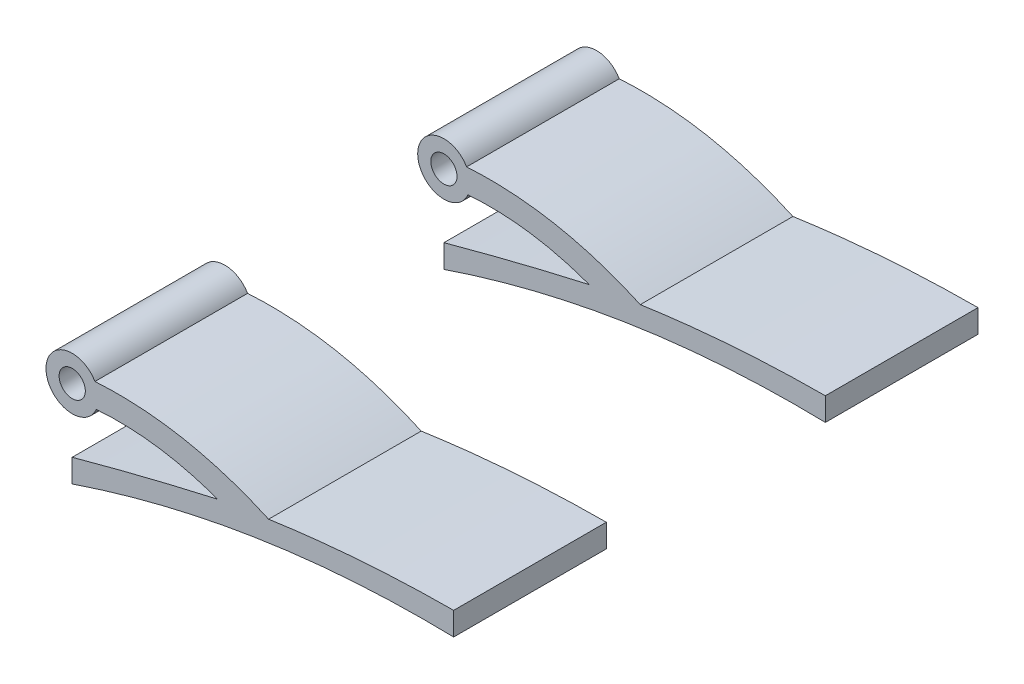
SolidWorks part; units mm, degrees
ref_plane "Front Plane" through (0, 0, 0) normal (0, 0, 1) x (1, 0, 0)
ref_plane "Top Plane" through (0, 0, 0) normal (0, 1, 0) x (1, 0, 0)
ref_plane "Right Plane" through (0, 0, 0) normal (1, 0, 0) x (0, 0, -1)
sketch "Sketch1" plane through (0, 0, 0) normal (0, 0, 1) x (1, 0, 0)
  circle A0 centre (0, 0) radius 25.4
  circle A1 centre (0, 0) radius 12.7
  dimension "D1" = 25.4
  dimension "D2" = 50.8
extrude "Boss-Extrude1" add sketch "Sketch1" along normal mid plane 508
sketch "Sketch3" plane through (0, 0, 0) normal (0, 0, 1) x (1, 0, 0)
  line L2 (0, -61.8729) -> (0, -84.2795)
  line L3 (369.5689, -5.5169) -> (369.5689, -27.9235)
  circle A0 centre (0, 0) radius 25.4 construction
  arc A2 (23.3186, -10.07) -> (21.997, 12.7) centre (0, 0) ccw
  spline S0 degree 2 poles (21.997, 12.7) (108.7753, 18.1925) (190.252, -18.7129) knots 0 0 0 1 1 1
  spline S1 degree 2 poles (23.3186, -10.07) (83.505, -5.4823) (140.7493, -26.6579) knots 0 0 0 1 1 1
  spline S2 degree 2 poles (190.252, -18.7129) (278.7121, -5.8166) (369.5689, -5.5169) knots 0.521873 0.521873 0.521873 1 1 1
  spline S3 degree 2 poles (0, -84.2795) (179.1543, -23.5221) (369.5689, -27.9235) knots 0 0 0 1 1 1
  spline S4 degree 2 poles (0, -61.8729) (69.9758, -42.6269) (140.7493, -26.6579) knots 0 0 0 1 1 1
extrude "Boss-Extrude2" add sketch "Sketch3" along normal mid plane 508
sketch "Sketch4" plane through (0, 0, 0) normal (0, 1, 0) x (1, 0, 0)
  line L0 (-25.4, 254) -> (-25.4, -254) construction
  line L1 (-25.4, 106.1108) -> (394.2926, 106.1108)
  line L2 (-25.4, 106.1108) -> (-25.4, -106.1108)
  line L3 (-25.4, -106.1108) -> (394.2926, -106.1108)
  line L4 (394.2926, 106.1108) -> (394.2926, -106.1108)
  point P8 (-25.4, 0)
extrude "Cut-Extrude2" cut sketch "Sketch4" against normal through all both and the other way through all
